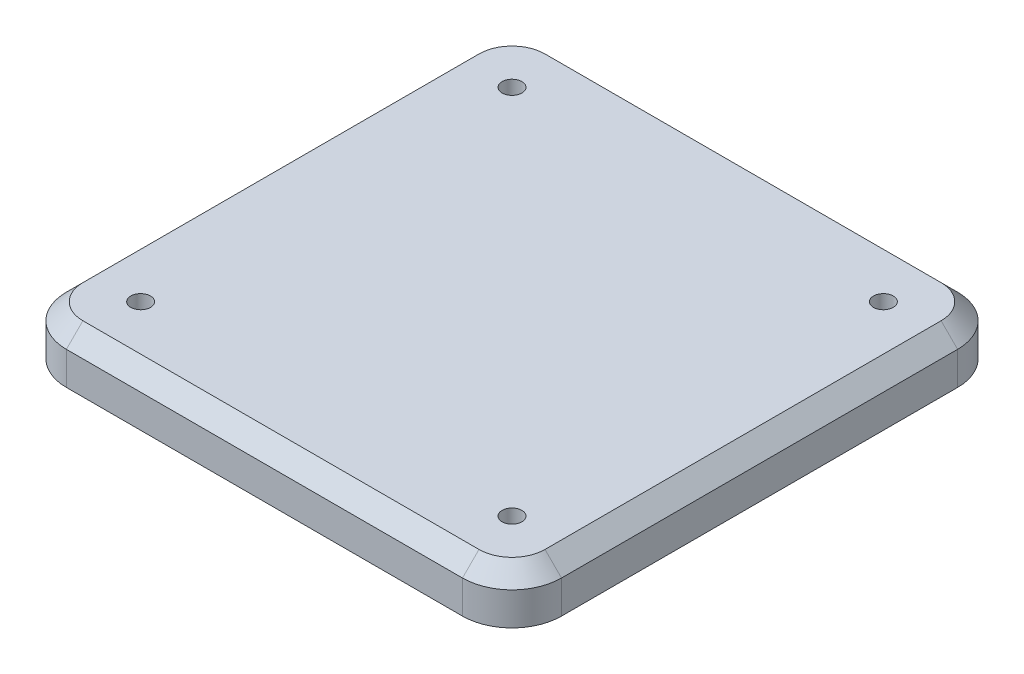
SolidWorks part; units mm, degrees
ref_plane "Front Plane" through (0, 0, 0) normal (0, 0, 1) x (1, 0, 0)
ref_plane "Top Plane" through (0, 0, 0) normal (0, 1, 0) x (1, 0, 0)
ref_plane "Right Plane" through (0, 0, 0) normal (1, 0, 0) x (0, 0, -1)
sketch "Sketch2" plane through (0, 0, 0) normal (0, 1, 0) x (1, 0, 0)
  line L0 (-120, 150) -> (120, 150)
  line L1 (150, 120) -> (150, -120)
  line L2 (120, -150) -> (-120, -150)
  line L3 (-150, -120) -> (-150, 120)
  line L4 (125, 150) -> (125, -150) construction
  line L5 (112.5, 150) -> (112.5, -150) construction
  line L6 (-150, 125) -> (150, 125) construction
  line L7 (-150, 112.5) -> (150, 112.5) construction
  line L8 (-150, 0) -> (150, 0) construction
  line L9 (0, 150) -> (0, -150) construction
  arc A0 (150, -120) -> (120, -150) centre (120, -120) cw
  arc A1 (-120, -150) -> (-150, -120) centre (-120, -120) cw
  arc A2 (-120, 150) -> (-150, 120) centre (-120, 120) ccw
  arc A3 (120, 150) -> (150, 120) centre (120, 120) cw
  point P3 (0, 150)
  point P5 (-150, 0)
  dimension "D2" = 30
  dimension "D1" = 300
  dimension "D3" = 37.5
  dimension "D4" = 25
  dimension "D5" = 37.5
  dimension "D6" = 25
extrude "Boss-Extrude1" add sketch "Sketch2" along normal mid plane 30
chamfer "Chamfer1" distance 10 angle 45 8 edges at (150, 15, 0) (141.2132, 15, -141.2132) (141.2132, 15, 141.2132) (0, 15, -150) (0, 15, 150) (-141.2132, 15, -141.2132) (-141.2132, 15, 141.2132) (-150, 15, 0)
sketch "Sketch12" plane through (0, 15, 0) normal (0, 1, 0) x (1, 0, 0)
  line L0 (-125, 150) -> (-125, -150) construction
  line L1 (-120, 150) -> (120, 150) construction
  line L2 (120, -150) -> (-120, -150) construction
  line L3 (-112.5, 150) -> (-112.5, -150) construction
  line L4 (-150, -112.5) -> (150, -112.5) construction
  line L5 (-150, -120) -> (-150, 120) construction
  line L6 (150, 120) -> (150, -120) construction
  line L7 (-150, -125) -> (150, -125) construction
  line L8 (0, 150) -> (0, -150) construction
  line L9 (-150, 0) -> (150, 0) construction
  circle A1 centre (-112.5, -112.5) radius 6
  circle A3 centre (112.5, -112.5) radius 6
  circle A4 centre (112.5, 112.5) radius 6
  circle A5 centre (-112.5, 112.5) radius 6
  dimension "D1" = 25
  dimension "D2" = 37.5
  dimension "D3" = 37.5
  dimension "D4" = 25
extrude "Cut-Extrude2" cut sketch "Sketch12" against normal offset from surface (10 mm away) 10 up to face at (0, 15, 0)
sketch "Sketch13" plane through (0, -15, 0) normal (0, -1, 0) x (1, 0, 0)
  line L0 (125, 150) -> (125, -150) construction
  line L1 (-120, 150) -> (120, 150) construction
  line L2 (120, -150) -> (-120, -150) construction
  line L3 (-150, 125) -> (150, 125) construction
  line L4 (-150, -120) -> (-150, 120) construction
  line L5 (150, 120) -> (150, -120) construction
  line L6 (0, 150) -> (0, -150) construction
  line L7 (-150, 0) -> (150, 0) construction
  circle A0 centre (125, 125) radius 6
  circle A1 centre (-125, 125) radius 6
  circle A2 centre (125, -125) radius 6
  circle A3 centre (-125, -125) radius 6
  dimension "D1" = 25
  dimension "D2" = 25
extrude "Cut-Extrude3" cut sketch "Sketch13" against normal offset from surface (10 mm away) 10 up to face at (0, -15, 0)
